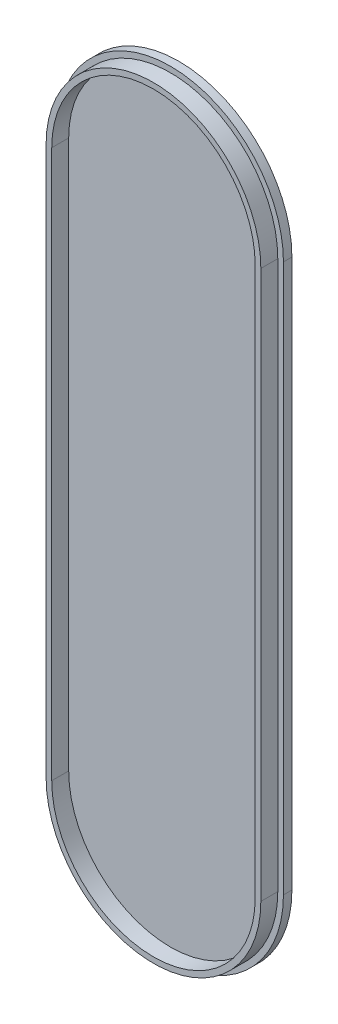
SolidWorks part; units mm, degrees
material "PLA"
ref_plane "Front Plane" through (0, 0, 0) normal (0, 0, 1) x (1, 0, 0)
ref_plane "Top Plane" through (0, 0, 0) normal (0, 1, 0) x (1, 0, 0)
ref_plane "Right Plane" through (0, 0, 0) normal (1, 0, 0) x (0, 0, -1)
sketch "Sketch3" plane through (0, 0, 0) normal (0, 0, 1) x (1, 0, 0)
  line L0 (-20, 0) -> (-20, -97)
  line L1 (20, 0) -> (20, -97)
  arc A0 (20, 0) -> (-20, 0) centre (0, 0) ccw
  arc A1 (-20, -97) -> (20, -97) centre (0, -97) ccw
  dimension "D1" = 40
  dimension "D3" = 20
  dimension "D2" = 97
extrude "Boss-Extrude1" add sketch "Sketch3" along normal blind 1.5
sketch "Sketch5" plane through (0, 0, 1.5) normal (0, 0, 1) x (1, 0, 0)
  line L5 (-18, 0) -> (-18, -97)
  line L6 (18, -97) -> (18, 0)
  line L7 (-19, 0) -> (-19, -97)
  line L8 (19, -97) -> (19, 0)
  line L9 (-19, 0) -> (-19, -97)
  line L10 (19, -97) -> (19, 0)
  arc A5 (18, 0) -> (-18, 0) centre (0, 0) ccw
  arc A6 (-18, -97) -> (18, -97) centre (0, -97) ccw
  arc A7 (-19, -97) -> (19, -97) centre (0, -97) ccw
  arc A8 (19, 0) -> (-19, 0) centre (0, 0) ccw
  arc A9 (-19, -97) -> (19, -97) centre (0, -97) ccw
  arc A10 (19, 0) -> (-19, 0) centre (0, 0) ccw
  dimension "D1" = 1
  dimension "D2" = 1
extrude "Boss-Extrude2" add sketch "Sketch5" along normal blind 3
sketch "Sketch6" plane through (0, 0, 0) normal (0, 0, -1) x (-1, 0, 0)
  circle A0 centre (0, -97) radius 18
  dimension "D1" = 36
